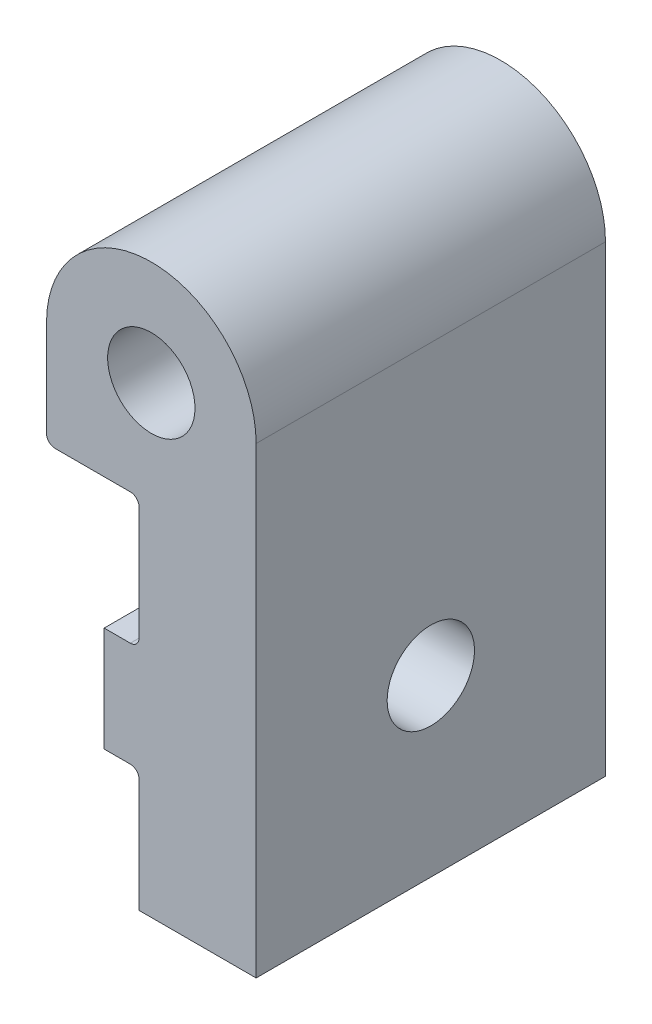
SolidWorks part; units mm, degrees
ref_plane "Front Plane" through (0, 0, 0) normal (0, 0, 1) x (1, 0, 0)
ref_plane "Top Plane" through (0, 0, 0) normal (0, 1, 0) x (1, 0, 0)
ref_plane "Right Plane" through (0, 0, 0) normal (1, 0, 0) x (0, 0, -1)
sketch "Sketch1" plane through (0, 0, 0) normal (0, 0, 1) x (1, 0, 0)
  line L0 (6.3, -53.6) -> (6.3, -59.6)
  line L1 (7.3, -53.6) -> (8.3, -53.6)
  line L2 (8.3, -53.6) -> (8.3, -53.1)
  line L3 (7.3, -59.6) -> (8.3, -59.6)
  line L4 (8.3, -59.6) -> (8.3, -60.1)
  line L10 (13.2426, -35.8574) -> (9.4645, -32.0792) construction
  line L11 (8, -28.5437) -> (8, 39.0289) construction
  line L12 (6.5355, 42.5645) -> (3, 46.1) construction
  line L13 (3, 46.1) -> (3, -46.1) construction
  line L14 (3, -46.1) -> (8.3, -46.1) construction
  line L15 (8.3, -46.6) -> (8.3, -46.1)
  line L16 (8.3, -46.1) -> (3, -46.1)
  line L17 (3, -46.1) -> (3, -40.1)
  line L18 (15, -40.1) -> (15, -66.6)
  line L19 (15, -66.6) -> (8.3, -66.6)
  line L120 (-11.7, -46.6) -> (-11.7, -53.1) construction
  line L121 (-11.7, -53.1) -> (-10.7, -53.1) construction
  line L122 (-10.7, -53.1) -> (-10.7, -53.6) construction
  line L123 (-10.7, -53.6) -> (-9.7, -53.6) construction
  line L124 (-9.7, -53.6) -> (-9.7, -51.1) construction
  line L125 (-9.7, -51.1) -> (-8.2607, -51.1) construction
  line L126 (-8.2607, -51.1) -> (-6.2007, -53.16) construction
  line L127 (-6.2007, -53.16) -> (-6.2007, -60.04) construction
  line L128 (-6.2007, -60.04) -> (-8.2607, -62.1) construction
  line L129 (-8.2607, -62.1) -> (-9.7, -62.1) construction
  line L130 (-9.7, -62.1) -> (-9.7, -59.6) construction
  line L131 (-9.7, -59.6) -> (-10.7, -59.6) construction
  line L132 (-10.7, -59.6) -> (-10.7, -60.1) construction
  line L133 (-10.7, -60.1) -> (-11.7, -60.1) construction
  line L134 (-11.7, -60.1) -> (-11.7, -66.6) construction
  line L135 (-11.7, -66.6) -> (-5.2, -66.6) construction
  line L136 (-5.2, -66.6) -> (-5.2, -65.6) construction
  line L137 (-5.2, -65.6) -> (-4.7, -65.6) construction
  line L138 (-4.7, -65.6) -> (-4.7, -64.6) construction
  line L139 (-4.7, -64.6) -> (-7.2, -64.6) construction
  line L140 (-7.2, -64.6) -> (-7.2, -63.1607) construction
  line L141 (-7.2, -63.1607) -> (-5.14, -61.1007) construction
  line L142 (-5.14, -61.1007) -> (1.74, -61.1007) construction
  line L143 (1.74, -61.1007) -> (3.8, -63.1607) construction
  line L144 (3.8, -63.1607) -> (3.8, -64.6) construction
  line L145 (3.8, -64.6) -> (1.3, -64.6) construction
  line L146 (1.3, -64.6) -> (1.3, -65.6) construction
  line L147 (1.3, -65.6) -> (1.8, -65.6) construction
  line L148 (1.8, -65.6) -> (1.8, -66.6) construction
  line L149 (1.8, -66.6) -> (8.3, -66.6) construction
  line L150 (8.3, -66.6) -> (8.3, -60.1)
  line L153 (7.3, -59.6) -> (6.3, -59.6)
  line L154 (6.3, -59.6) -> (6.3, -62.1) construction
  line L155 (6.3, -62.1) -> (4.8607, -62.1) construction
  line L156 (4.8607, -62.1) -> (2.8007, -60.04) construction
  line L157 (2.8007, -60.04) -> (2.8007, -53.16) construction
  line L158 (2.8007, -53.16) -> (4.8607, -51.1) construction
  line L159 (4.8607, -51.1) -> (6.3, -51.1) construction
  line L160 (6.3, -51.1) -> (6.3, -53.6) construction
  line L161 (6.3, -53.6) -> (7.3, -53.6)
  line L164 (8.3, -53.1) -> (8.3, -46.6)
  line L165 (8.3, -46.6) -> (1.8, -46.6) construction
  line L166 (1.8, -46.6) -> (1.8, -47.6) construction
  line L167 (1.8, -47.6) -> (1.3, -47.6) construction
  line L168 (1.3, -47.6) -> (1.3, -48.6) construction
  line L169 (1.3, -48.6) -> (3.8, -48.6) construction
  line L170 (3.8, -48.6) -> (3.8, -50.0393) construction
  line L171 (3.8, -50.0393) -> (1.74, -52.0993) construction
  line L172 (1.74, -52.0993) -> (-5.14, -52.0993) construction
  line L173 (-5.14, -52.0993) -> (-7.2, -50.0393) construction
  line L174 (-7.2, -50.0393) -> (-7.2, -48.6) construction
  line L175 (-7.2, -48.6) -> (-4.7, -48.6) construction
  line L176 (-4.7, -48.6) -> (-4.7, -47.6) construction
  line L177 (-4.7, -47.6) -> (-5.2, -47.6) construction
  line L178 (-5.2, -47.6) -> (-5.2, -46.6) construction
  line L179 (-5.2, -46.6) -> (-11.7, -46.6) construction
  circle A1 centre (9, -40.1) radius 2.5
  arc A2 (15, -40.1) -> (3, -40.1) centre (9, -40.1) ccw
  arc A6 (15, -40.1) -> (13.2426, -35.8574) centre (9, -40.1) ccw construction
  arc A7 (8, -28.5437) -> (9.4645, -32.0792) centre (13, -28.5437) ccw construction
  arc A8 (8, 39.0289) -> (6.5355, 42.5645) centre (3, 39.0289) ccw construction
extrude "Boss-Extrude1" add sketch "Sketch1" along normal blind 20
sketch "Sketch2" plane through (6.3, 0, 0) normal (-1, 0, 0) x (0, 0, 1)
  line L0 (10, -56.6) -> (10, -66.6) construction
  line L1 (20, -66.6) -> (0, -66.6) construction
  line L2 (10, -56.6) -> (20, -56.6) construction
  line L3 (20, -53.6) -> (20, -59.6) construction
  circle A0 centre (10, -56.6) radius 2.5
  dimension "D1" = 5
extrude "Cut-Extrude1" cut sketch "Sketch2" against normal blind 20
sketch "Sketch3" plane through (6.3, 0, 0) normal (-1, 0, 0) x (0, 0, 1)
  line L0 (20, -53.6) -> (0, -53.6) construction
  line L1 (5, -53.6) -> (15, -53.6)
  line L2 (5, -53.6) -> (5, -59.6)
  line L3 (5, -59.6) -> (15, -59.6)
  line L4 (15, -53.6) -> (15, -59.6)
  line L5 (20, -59.6) -> (0, -59.6) construction
  line L6 (10, -56.6) -> (10, -59.6) construction
  dimension "D1" = 10
extrude "Cut-Extrude2" cut sketch "Sketch3" against normal blind 2
fillet "Fillet1" radius 0.5 2 edges at (8.3, -46.1, 10) (3, -46.1, 10)
fillet "Fillet2" radius 0.5 4 edges at (8.3, -59.6, 2.5) (8.3, -59.6, 17.5) (8.3, -53.6, 17.5) (8.3, -53.6, 2.5)
